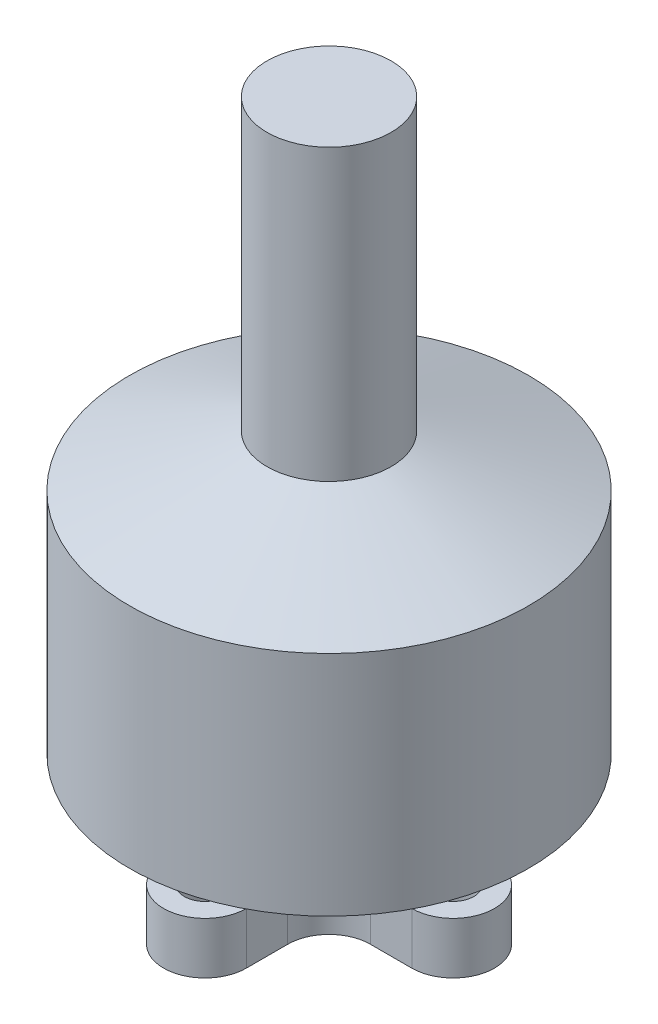
SolidWorks part; units mm, degrees
material "MotorMat"
ref_plane "Front Plane" through (0, 0, 0) normal (0, 0, 1) x (1, 0, 0)
ref_plane "Top Plane" through (0, 0, 0) normal (0, 1, 0) x (1, 0, 0)
ref_plane "Right Plane" through (0, 0, 0) normal (1, 0, 0) x (0, 0, -1)
sketch "Sketch1" plane through (0, 0, 0) normal (0, 1, 0) x (1, 0, 0)
  line L0 (-6, -2) -> (6, -2)
  line L1 (6, 2) -> (-6, 2)
  line L2 (-2, 6) -> (-2, -6)
  line L3 (2, -6) -> (2, 6)
  circle A1 centre (0, 0) radius 6 construction
  circle A2 centre (-6, 0) radius 1
  circle A3 centre (0, 6) radius 1
  circle A4 centre (6, 0) radius 1
  circle A5 centre (0, -6) radius 1
  circle A6 centre (0, 6) radius 2
  circle A7 centre (-6, 0) radius 2
  circle A8 centre (0, -6) radius 2
  circle A9 centre (6, 0) radius 2
  dimension "D1" = 12
  dimension "D2" = 2
  dimension "D3" = 2
  dimension "D4" = 2
  dimension "D5" = 2
  dimension "D7" = 4
  dimension "D8" = 4
  dimension "D9" = 4
  dimension "D10" = 4
extrude "Boss-Extrude1" add sketch "Sketch1" along normal blind 2.5 contours L0 L3 L1 L2 | A7 L0 L2 L1 | A7 A2 | A8 A5 | A8 L3 L0 L2 | A6 L2 L1 L3 | A6 A3 | A9 L1 L3 L0 | A9 A4
fillet "Fillet1" radius 2 4 edges at (-2, 1.25, -2) (2, 1.25, -2) (2, 1.25, 2) (-2, 1.25, 2)
sketch "Sketch2" plane through (0, 2.5, 0) normal (0, 1, 0) x (1, 0, 0)
  circle A0 centre (0, 0) radius 3.5
  dimension "D1" = 7
sketch "Sketch3" plane through (0, 0, 0) normal (0, 0, 1) x (1, 0, 0)
  line L0 (0, 2.5) -> (0, 39.2203) construction
  line L1 (3.5, 2.5) -> (-3.5, 2.5) construction
  line L2 (0, 2.5) -> (3.5, 2.5)
  line L3 (3.5, 2.5) -> (3.5, 5)
  line L4 (3.5, 5) -> (9.65, 5)
  line L5 (9.65, 5) -> (9.65, 16)
  line L6 (9.65, 16) -> (3, 18.5)
  line L7 (3, 18.5) -> (3, 32.5)
  line L8 (3, 32.5) -> (0, 32.5)
  line L9 (0, 32.5) -> (0, 2.5)
  point P5 (0, 39.2203)
  dimension "D1" = 2.5
  dimension "D2" = 19.3
  dimension "D3" = 11
  dimension "D4" = 2.5
  dimension "D5" = 6
  dimension "D6" = 14
revolve "Revolve1" add sketch "Sketch3" angle 360 about L0
